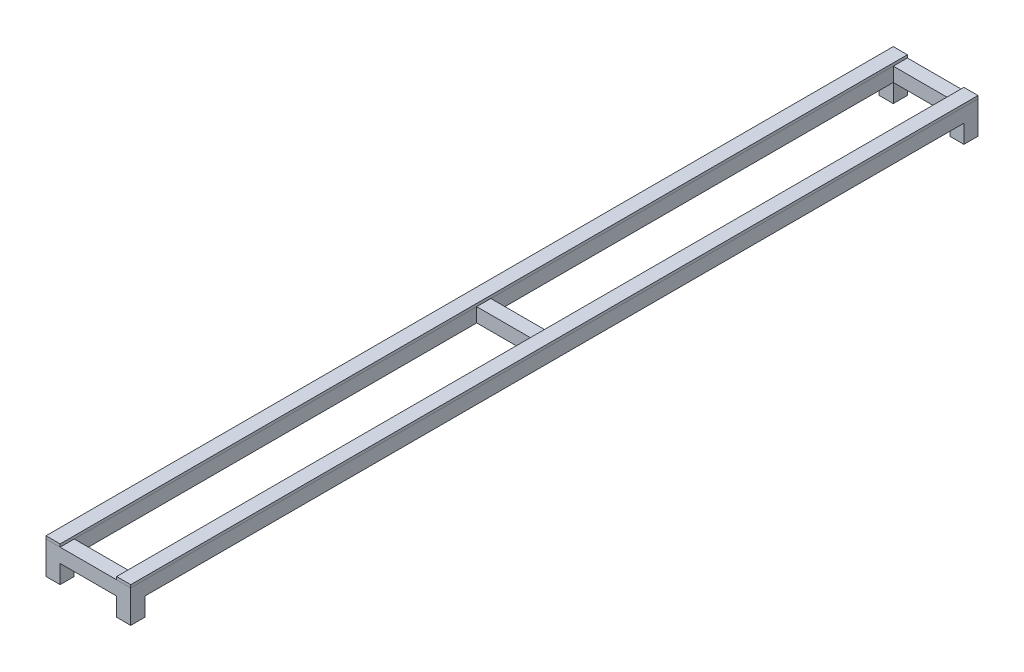
SolidWorks part; units mm, degrees
ref_plane "前视基准面" through (0, 0, 0) normal (0, 0, 1) x (1, 0, 0)
ref_plane "上视基准面" through (0, 0, 0) normal (0, 1, 0) x (1, 0, 0)
ref_plane "右视基准面" through (0, 0, 0) normal (1, 0, 0) x (0, 0, -1)
sketch "草图1" plane through (0, 0, 0) normal (0, 0, 1) x (1, 0, 0)
  line L0 (0, 0) -> (0, 278.7234) construction
  line L1 (0, 0) -> (-250, 0) construction
  line L3 (-300, 50) -> (-200, 50)
  line L4 (-300, 50) -> (-300, -50)
  line L5 (-300, -50) -> (-200, -50)
  line L6 (-200, 50) -> (-200, -50)
  line L7 (-300, 50) -> (-200, -50) construction
  line L8 (-300, -50) -> (-200, 50) construction
  line L9 (200, 50) -> (300, 50)
  line L10 (200, 50) -> (200, -50)
  line L11 (200, -50) -> (300, -50)
  line L12 (300, 50) -> (300, -50)
  line L13 (200, 50) -> (300, -50) construction
  line L14 (200, -50) -> (300, 50) construction
  point P8 (250, 0)
  dimension "D1" = 100
  dimension "D2" = 600
extrude "凸台-拉伸1" add sketch "草图1" along normal mid plane 6000
sketch "草图2" plane through (300, 0, 0) normal (1, 0, 0) x (0, 0, -1)
  line L0 (-3000, 50) -> (3000, 50) construction
  line L1 (-3000, 50) -> (-2900, 50)
  line L2 (-3000, 50) -> (-3000, -50)
  line L3 (-3000, -50) -> (-2900, -50)
  line L4 (-2900, 50) -> (-2900, -50)
  line L5 (-3000, -50) -> (3000, -50) construction
  line L7 (2900, 50) -> (3000, 50)
  line L8 (2900, 50) -> (2900, -50)
  line L9 (2900, -50) -> (3000, -50)
  line L10 (3000, 50) -> (3000, -50)
  line L11 (-50, 50) -> (50, 50)
  line L12 (-50, 50) -> (-50, -50)
  line L13 (-50, -50) -> (50, -50)
  line L14 (50, 50) -> (50, -50)
  line L15 (-50, 50) -> (50, -50) construction
  line L16 (-50, -50) -> (50, 50) construction
  line L18 (-3000, -50) -> (-3000, 50) construction
  line L19 (3000, -50) -> (3000, 50) construction
  point P12 (0, 0)
extrude "凸台-拉伸2" add sketch "草图2" against normal up to surface (500 mm away) up to face at (-200, 0, 0)
sketch "草图3" plane through (0, -50, 0) normal (0, -1, 0) x (1, 0, 0)
  line L0 (300, 3000) -> (300, -3000) construction
  line L1 (200, 3000) -> (300, 3000)
  line L2 (200, 3000) -> (200, 2900)
  line L3 (200, 2900) -> (300, 2900)
  line L4 (300, 3000) -> (300, 2900)
  line L5 (-300, 3000) -> (-300, -3000) construction
  line L6 (-200, 3000) -> (-300, 3000)
  line L7 (-200, 3000) -> (-200, 2900)
  line L8 (-200, 2900) -> (-300, 2900)
  line L9 (-300, 3000) -> (-300, 2900)
  line L11 (-300, 3000) -> (300, 3000) construction
  line L12 (-300, 3000) -> (-300, -3000) construction
  line L19 (200, -2900) -> (300, -2900)
  line L20 (200, -2900) -> (200, -3000)
  line L21 (200, -3000) -> (300, -3000)
  line L22 (300, -2900) -> (300, -3000)
  line L23 (-200, -2900) -> (-300, -2900)
  line L24 (-200, -2900) -> (-200, -3000)
  line L25 (-200, -3000) -> (-300, -3000)
  line L26 (-300, -2900) -> (-300, -3000)
  point P14 (0, 0)
  point P15 (300, 3000)
  point P16 (0, 0)
  point P17 (-300, 3000)
  point P34 (0, 0)
extrude "凸台-拉伸3" add sketch "草图3" along normal blind 130
sketch "草图4" plane through (0, 50, 0) normal (0, 1, 0) x (1, 0, 0)
  line L1 (200, -3000) -> (300, -3000)
  line L2 (200, -3000) -> (200, 3000)
  line L3 (200, 3000) -> (300, 3000)
  line L4 (300, -3000) -> (300, 3000)
  line L5 (-200, 3000) -> (-300, 3000)
  line L6 (-200, 3000) -> (-200, -3000)
  line L7 (-200, -3000) -> (-300, -3000)
  line L8 (-300, 3000) -> (-300, -3000)
  point P10 (0, 0)
  point P11 (-200, 3000)
  point P15 (0, 0)
  point P16 (200, -3000)
  point P18 (300, -3000)
extrude "凸台-拉伸4" add sketch "草图4" along normal blind 20 separate body
equation "\"零件重量\"= \"SW-质量\""
